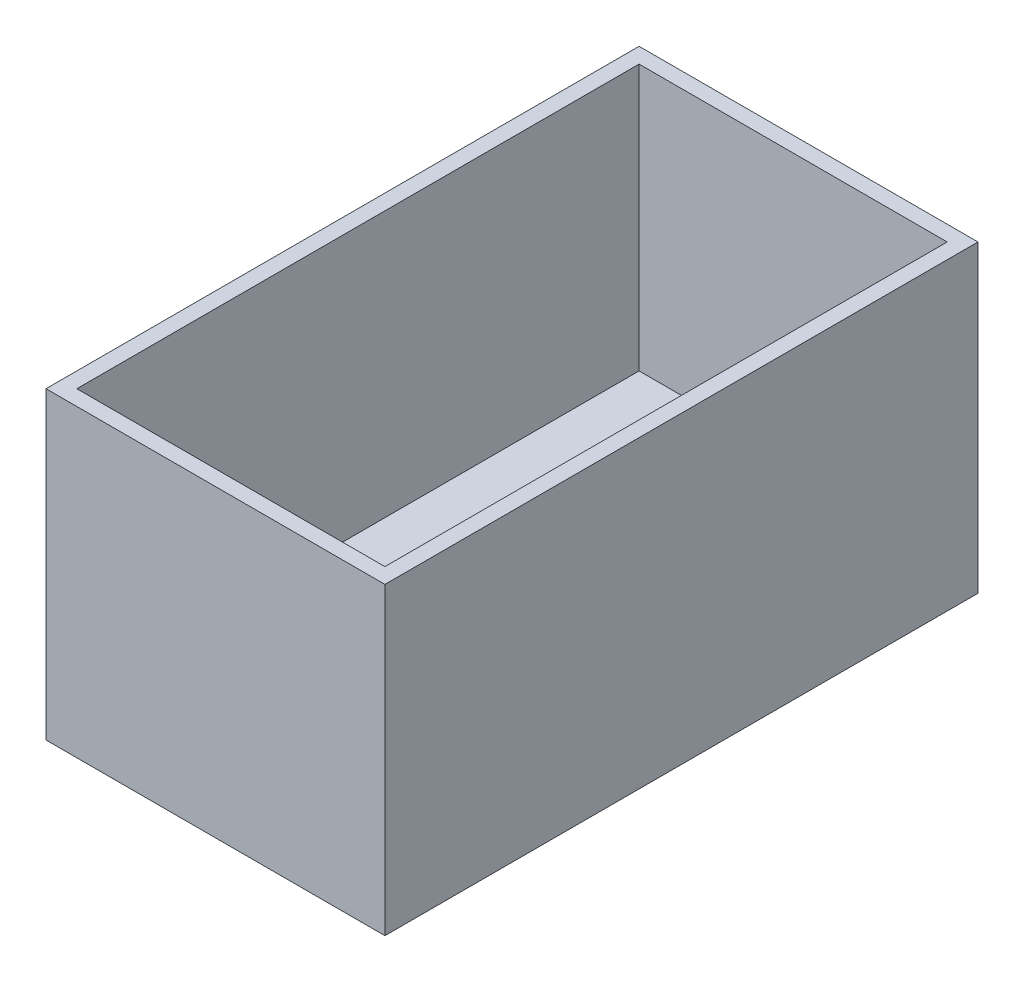
SolidWorks part; units mm, degrees
material "petg"
ref_plane "前视基准面" through (0, 0, 0) normal (0, 0, 1) x (1, 0, 0)
ref_plane "上视基准面" through (0, 0, 0) normal (0, 1, 0) x (1, 0, 0)
ref_plane "右视基准面" through (0, 0, 0) normal (1, 0, 0) x (0, 0, -1)
other "Configuration Table"
sketch "草图1" plane through (0, 0, 0) normal (0, 0, 1) x (1, 0, 0)
  line L0 (-17.8281, 6.526) -> (-17.8281, -32.974)
  line L1 (-17.8281, -32.974) -> (26.1719, -32.974)
  line L2 (26.1719, -32.974) -> (26.1719, 6.526)
  line L3 (26.1719, 6.526) -> (24.1719, 6.526)
  line L4 (24.1719, 6.526) -> (24.1719, -27.974)
  line L5 (24.1719, -27.974) -> (-15.8281, -27.974)
  line L6 (-15.8281, -27.974) -> (-15.8281, 6.526)
  line L7 (-15.8281, 6.526) -> (-17.8281, 6.526)
  dimension "D1" = 40
  dimension "D2" = 2
  dimension "D3" = 2
  dimension "D4" = 5
  dimension "D5" = 34.5
  dimension "D6" = 34.5
extrude "凸台-拉伸1" add sketch "草图1" along normal blind 73
sketch "草图2" plane through (0, 0, 73) normal (0, 0, 1) x (1, 0, 0)
  line L0 (-17.8281, 6.526) -> (26.1719, 6.526)
  line L8 (-15.8281, 6.526) -> (-17.8281, 6.526)
  line L9 (-17.8281, 6.526) -> (-17.8281, -32.974)
  line L10 (-17.8281, -32.974) -> (26.1719, -32.974)
  line L11 (26.1719, -32.974) -> (26.1719, 6.526)
  line L12 (26.1719, 6.526) -> (24.1719, 6.526)
  line L13 (24.1719, 6.526) -> (24.1719, -27.974)
  line L14 (24.1719, -27.974) -> (-15.8281, -27.974)
  line L15 (-15.8281, -27.974) -> (-15.8281, 6.526)
  line L17 (-17.8281, 6.526) -> (-17.8281, -32.974)
  line L18 (-17.8281, -32.974) -> (26.1719, -32.974)
  line L19 (26.1719, -32.974) -> (26.1719, 6.526)
  dimension "D1" = 0
extrude "凸台-拉伸2" add sketch "草图2" along normal blind 2
sketch "草图3" plane through (0, 0, 0) normal (0, 0, -1) x (-1, 0, 0)
  line L0 (-26.1719, 6.526) -> (17.8281, 6.526)
  line L8 (17.8281, 6.526) -> (15.8281, 6.526)
  line L9 (15.8281, 6.526) -> (15.8281, -27.974)
  line L10 (15.8281, -27.974) -> (-24.1719, -27.974)
  line L11 (-24.1719, -27.974) -> (-24.1719, 6.526)
  line L12 (-24.1719, 6.526) -> (-26.1719, 6.526)
  line L13 (-26.1719, 6.526) -> (-26.1719, -32.974)
  line L14 (-26.1719, -32.974) -> (17.8281, -32.974)
  line L15 (17.8281, -32.974) -> (17.8281, 6.526)
  line L21 (-26.1719, 6.526) -> (-26.1719, -32.974)
  line L22 (-26.1719, -32.974) -> (17.8281, -32.974)
  line L23 (17.8281, -32.974) -> (17.8281, 6.526)
  dimension "D1" = 0
extrude "凸台-拉伸3" add sketch "草图3" along normal blind 2
sketch "草图4" plane through (0, -27.974, 0) normal (0, 1, 0) x (1, 0, 0)
  line L0 (4.1719, 0) -> (4.1719, -50000) construction
  line L1 (-15.8281, 0) -> (24.1719, 0) construction
  line L2 (24.1719, -36.5) -> (-49975.8281, -36.5) construction
  line L3 (24.1719, -73) -> (24.1719, 0) construction
  circle A0 centre (4.1719, -26.5) radius 2.75
  circle A1 centre (4.1719, -46.5) radius 2.75
  circle A2 centre (4.1719, -11.5) radius 2.75
  circle A3 centre (4.1719, -61.5) radius 2.75
  point P4 (4.1719, 0)
  point P9 (24.1719, -36.5)
  dimension "D1" = 5.5
  dimension "D2" = 5.5
  dimension "D3" = 10
  dimension "D4" = 10
  dimension "D5" = 15
  dimension "D6" = 5.5
  dimension "D7" = 15
extrude "切除-拉伸1" cut sketch "草图4" against normal blind 10
sketch "草图5" plane through (0, -27.974, 0) normal (0, 1, 0) x (1, 0, 0)
  circle A0 centre (4.1719, -61.5) radius 2.75 construction
  circle A1 centre (4.1719, -46.5) radius 2.75 construction
  circle A2 centre (4.1719, -26.5) radius 2.75 construction
  circle A3 centre (4.1719, -11.5) radius 2.75 construction
  circle A4 centre (4.1719, -61.5) radius 2.75
  circle A5 centre (4.1719, -46.5) radius 2.75
  circle A6 centre (4.1719, -26.5) radius 2.75
  circle A7 centre (4.1719, -11.5) radius 2.75
  circle A8 centre (4.1719, -61.5) radius 5.75
  circle A9 centre (4.1719, -46.5) radius 5.75
  circle A10 centre (4.1719, -26.5) radius 5.75
  circle A11 centre (4.1719, -11.5) radius 5.75
  dimension "D1" = 3
extrude "切除-拉伸2" cut sketch "草图5" against normal blind 3
